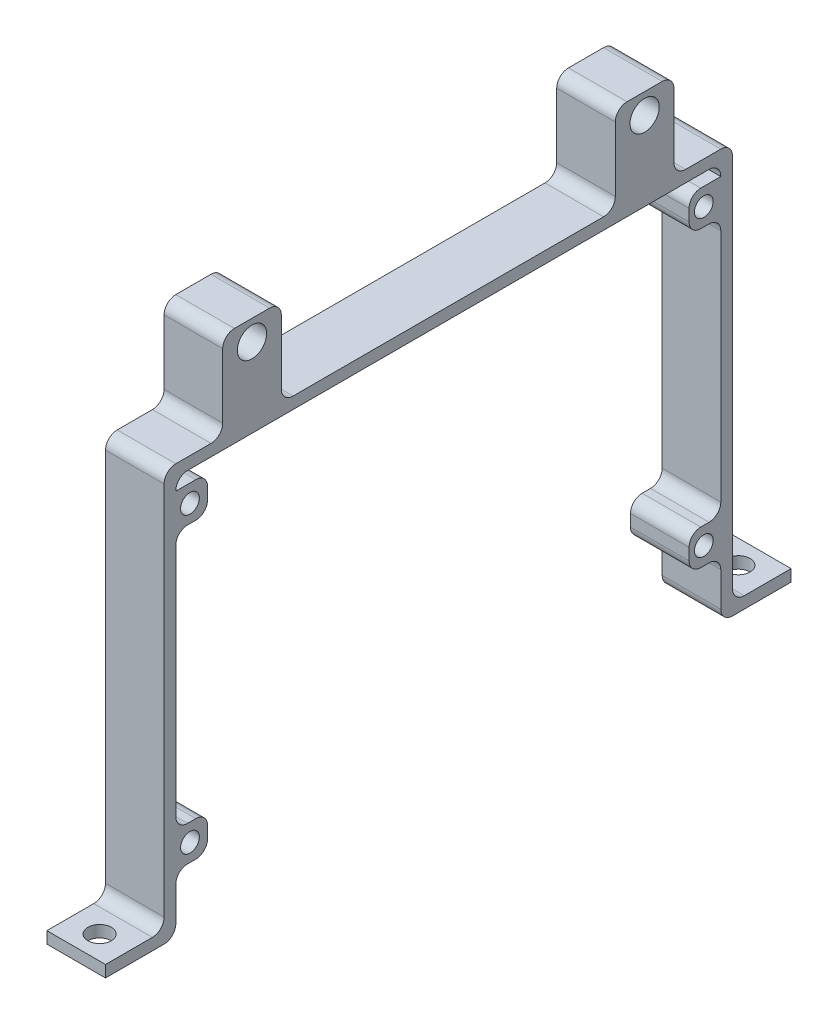
SolidWorks part; units mm, degrees
ref_plane "Front Plane" through (0, 0, 0) normal (0, 0, 1) x (1, 0, 0)
ref_plane "Top Plane" through (0, 0, 0) normal (0, 1, 0) x (1, 0, 0)
ref_plane "Right Plane" through (0, 0, 0) normal (1, 0, 0) x (0, 0, -1)
sketch "Sketch1" plane through (0, 0, 0) normal (1, 0, 0) x (0, 0, -1)
  line L0 (-58.5, 0) -> (-46.5, 0)
  line L1 (-46.5, 0) -> (-46.5, 68)
  line L2 (-46.5, 68) -> (0, 68)
  line L3 (0, 0) -> (0, 68) construction
  line L4 (-58.5, 2) -> (-48.5, 2)
  line L5 (-48.5, 2) -> (-48.5, 70)
  line L6 (-48.5, 70) -> (0, 70)
  line L7 (-58.5, 0) -> (-58.5, 2)
  line L8 (0, 68) -> (0, 70)
  line L9 (-53.5, 2) -> (-53.5, 0) construction
  line L11 (-38.5, 70) -> (-28.5, 70)
  line L12 (-38.5, 70) -> (-38.5, 85)
  line L13 (-38.5, 85) -> (-28.5, 85)
  line L14 (-28.5, 70) -> (-28.5, 85)
  circle A0 centre (-33.5, 81.5) radius 2.5
  point P18 (-33.4473, 78.3604)
  dimension "D8" = 5
  dimension "D2" = 53.5
  dimension "D3" = 10
  dimension "D4" = 70
  dimension "D5" = 10
  dimension "D6" = 15
  dimension "D7" = 10
  dimension "D9" = 3.5
  dimension "D10" = 5
  dimension "D1" = 2
extrude "Boss-Extrude1" add sketch "Sketch1" along normal blind 10 contours L6 L14 L13 L12 A0 | L2 L8 L6 L5 L4 L7 L0 L1
fillet "Fillet1" radius 2 3 edges at (5, 70, 48.5) (5, 68, 46.5) (5, 2, 48.5)
hole_wizard "Ø4.0mm Dowel Hole1" positions "3DSketch1" profile "Sketch2" hole size "Ø4.0" standard "DIN" end condition through all
sketch3d "3DSketch1"
  line L0 (5, 2, 54.5) -> (5, 2, 50.5) construction
  line L1 (10, 2, 50.5) -> (0, 2, 50.5) construction
  line L3 (5, 2, 54.5) -> (10, 2, 54.5) construction
  point P0 (5, 2, 54.5)
  point P13 (0, 0, 0)
sketch "Sketch2" plane through (5, 2, 54.5) normal (1, 0, 0) x (0, 0, 1)
  line L0 (0, 0) -> (0, 2)
  line L1 (0, 2) -> (2, 2)
  line L2 (2, 2) -> (2, 0)
  line L5 (2, 0) -> (0, 0)
  line L11 (0, -6.35) -> (0, 107.95) construction
  dimension "Thru Hole Dia." = 4
  dimension "Thru Hole Depth" = 2
sketch "Sketch4" plane through (10, 0, 0) normal (1, 0, 0) x (0, 0, -1)
  line L7 (-41.0835, 15.8524) -> (-46.5, 15.8524)
  line L8 (-41.0835, 15.8524) -> (-41.0835, 9.8524)
  line L10 (-41.0835, 9.8524) -> (-46.5, 9.8524)
  line L11 (-41.0835, 15.8524) -> (-46.5, 10.4359) construction
  line L12 (-45.2149, 13.9838) -> (-41.0835, 9.8524) construction
  line L14 (-46.5, 0) -> (-46.5, 66) construction
  line L15 (-41.0835, 59.9464) -> (-47.0835, 59.9464)
  line L18 (-41.0835, 59.9464) -> (-41.0835, 65.9464)
  line L19 (-47.0835, 59.9464) -> (-47.0835, 65.9464)
  line L20 (-41.0835, 65.9464) -> (-47.0835, 65.9464)
  line L21 (-41.0835, 59.9464) -> (-47.0835, 65.9464) construction
  line L22 (-47.0835, 59.9464) -> (-41.0835, 65.9464) construction
  line L24 (-46.5, 0) -> (-46.5, 66)
  circle A0 centre (-44.0835, 12.8524) radius 1.6
  circle A1 centre (-44.0835, 12.8524) radius 1.6 construction
  circle A3 centre (-44.0835, 62.9464) radius 1.6 construction
  circle A5 centre (-44.0835, 62.9464) radius 1.6
  dimension "D2" = 6
  dimension "D1" = 6
  dimension "D3" = 3
extrude "Boss-Extrude2" add sketch "Sketch4" against normal up to surface (10 mm away)
mirror "Mirror1" about plane through (0, 0, 0) normal (0, 0, 1) of "Boss-Extrude1", "Ø4.0mm Dowel Hole1", "Fillet1"
sketch "Sketch5" plane through (10, 0, 0) normal (1, 0, 0) x (0, 0, -1)
  line L0 (46.5, 0) -> (46.5, 66) construction
  line L2 (46.5, 0) -> (46.5, 66)
  line L7 (46.5, 65.9464) -> (46.5, 66)
  line L8 (41.0835, 65.9464) -> (46.5, 65.9464)
  line L9 (41.0835, 59.9464) -> (41.0835, 65.9464)
  line L10 (46.5, 59.9464) -> (41.0835, 59.9464)
  line L11 (46.5, 15.8524) -> (46.5, 59.9464)
  line L12 (41.0835, 15.8524) -> (46.5, 15.8524)
  line L13 (41.0835, 9.8524) -> (41.0835, 15.8524)
  line L14 (46.5, 9.8524) -> (41.0835, 9.8524)
  circle A18 centre (43.6025, 12.8524) radius 1.6
  circle A19 centre (43.6025, 62.9464) radius 1.6
  point P46 (0, 0)
extrude "Boss-Extrude3" add sketch "Sketch5" against normal up to surface (10 mm away)
fillet "Fillet2" radius 2 24 edges at (5, 70, -38.5) (5, 70, -28.5) (5, 85, -28.5) (5, 70, 38.5) (5, 70, 28.5) (5, 59.9464, 46.5) (5, 15.8524, 46.5) (5, 9.8524, 46.5) (5, 59.9464, -46.5) (5, 9.8524, -46.5) (5, 15.8524, -46.5) (5, 15.8524, -41.0835) (5, 9.8524, -41.0835) (5, 0, -46.5) (5, 59.9464, -41.0835) (5, 65.9464, -41.0835) (5, 0, 46.5) (5, 85, -38.5) (5, 85, 38.5) (5, 85, 28.5) (5, 59.9464, 41.0835) (5, 65.9464, 41.0835) (5, 15.8524, 41.0835) (5, 9.8524, 41.0835)
